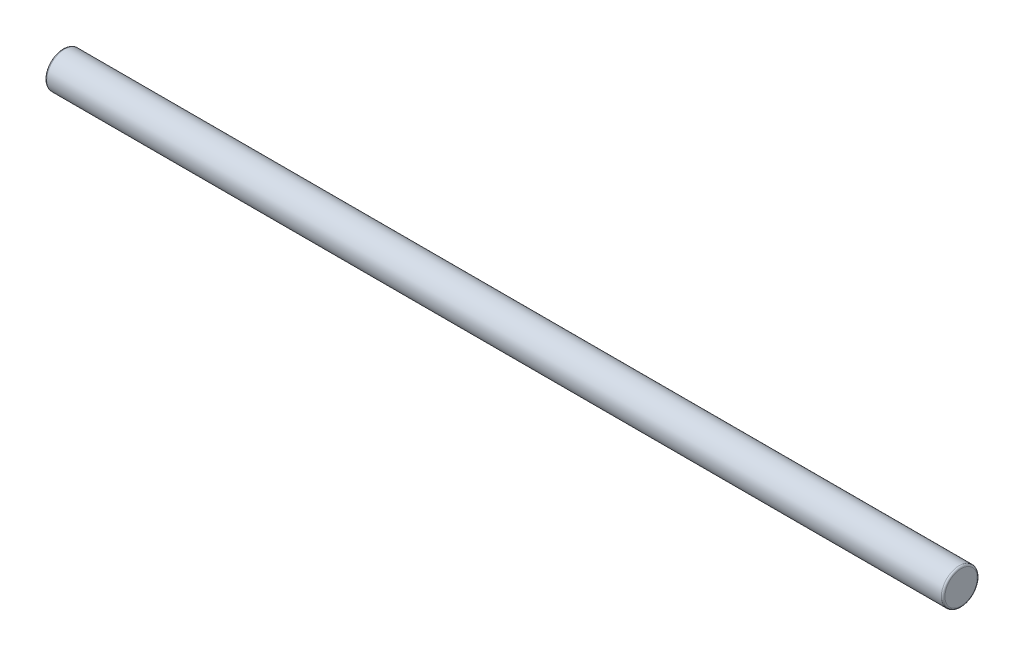
SolidWorks part; units mm, degrees
material "201 Acero inoxidable recocido (SS)"
ref_plane "Alzado" through (0, 0, 0) normal (0, 0, 1) x (1, 0, 0)
ref_plane "Planta" through (0, 0, 0) normal (0, 1, 0) x (1, 0, 0)
ref_plane "Vista lateral" through (0, 0, 0) normal (1, 0, 0) x (0, 0, -1)
sketch "Croquis1" plane through (0, 0, 0) normal (1, 0, 0) x (0, 0, -1)
  circle A0 centre (0, 0) radius 10
  dimension "D1" = 20
extrude "Saliente-Extruir1" add sketch "Croquis1" along normal mid plane 500
fillet "Redondeo1" radius 1 2 edges at (-250, 0, -10) (250, 0, -10)
